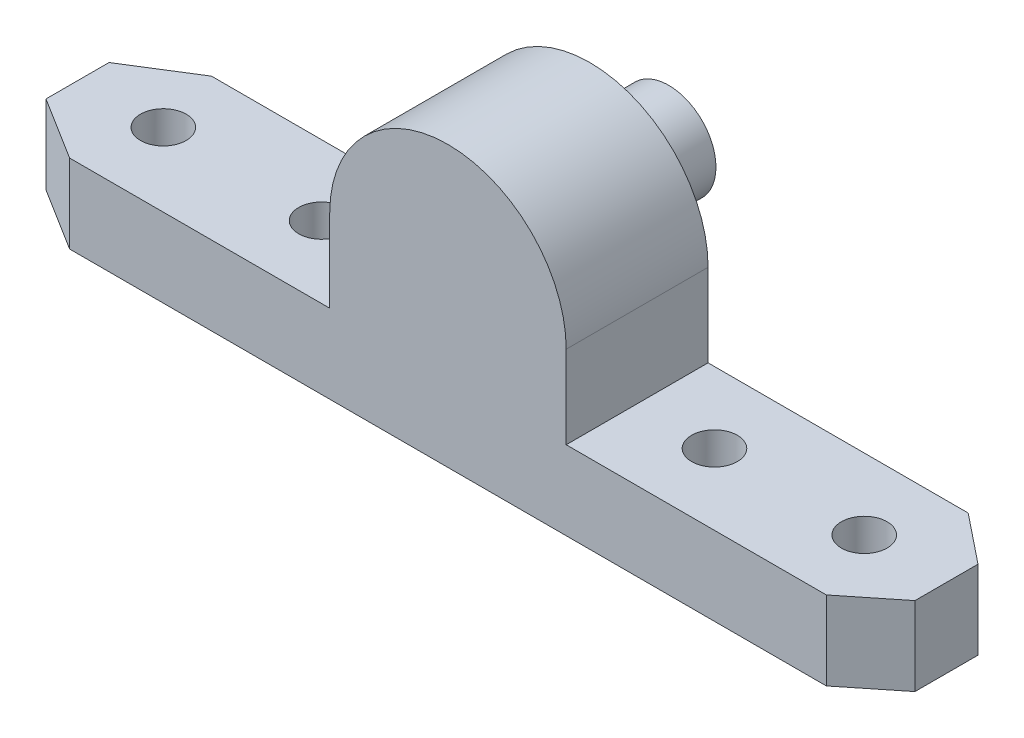
SolidWorks part; units mm, degrees
ref_plane "Płaszczyzna przednia" through (0, 0, 0) normal (0, 0, 1) x (1, 0, 0)
ref_plane "Płaszczyzna górna" through (0, 0, 0) normal (0, 1, 0) x (1, 0, 0)
ref_plane "Płaszczyzna prawa" through (0, 0, 0) normal (1, 0, 0) x (0, 0, -1)
sketch "Szkic1" plane through (0, 0, 0) normal (0, 1, 0) x (1, 0, 0)
  line L0 (24, 4.5) -> (27.1225, 2)
  line L1 (27.1225, 2) -> (27.1225, -2)
  line L2 (-24, -4.5) -> (24, -4.5)
  line L4 (-24, 4.5) -> (24, 4.5)
  line L6 (-24, -4.5) -> (24, 4.5) construction
  line L7 (-24, 4.5) -> (24, -4.5) construction
  line L8 (27.1225, -2) -> (24, -4.5)
  line L9 (-24, 4.5) -> (-28, 2)
  line L10 (-28, 2) -> (-28, -2)
  line L11 (-28, -2) -> (-24, -4.5)
  point P1 (0, 0)
  dimension "D3" = 4
  dimension "D1" = 48
  dimension "D2" = 9
  dimension "D4" = 4
  dimension "D5" = 4
  dimension "D6" = 4
  dimension "D7" = 4
  dimension "D8" = 4
extrude "Dodanie-wyciągnięcie1" add sketch "Szkic1" along normal blind 5
sketch "Szkic2" plane through (0, 0, 4.5) normal (0, 0, 1) x (1, 0, 0)
  line L0 (-24, 5) -> (24, 5) construction
  line L1 (-7.5, 5) -> (7.5, 5)
  line L2 (-7.5, 5) -> (-7.5, 10.25)
  line L4 (7.5, 10.25) -> (7.5, 5)
  arc A0 (-7.5, 10.25) -> (7.5, 10.25) centre (0, 10.25) cw
  point P7 (0, 5)
  dimension "D3" = 7.5
  dimension "D1" = 15
  dimension "D2" = 5.25
extrude "Dodanie-wyciągnięcie2" add sketch "Szkic2" against normal blind 9
sketch "Szkic3" plane through (0, 0, 4.5) normal (0, 0, 1) x (1, 0, 0)
  line L0 (0, 0) -> (0, 11) construction
  line L1 (-24, 0) -> (24, 0) construction
  circle A0 centre (0, 11) radius 3
  dimension "D2" = 6
  dimension "D1" = 11
sketch "Szkic4" plane through (0, 5, 0) normal (0, 1, 0) x (1, 0, 0)
  line L0 (27.1225, 0) -> (7.5, 0) construction
  line L1 (27.1225, -2) -> (27.1225, 2) construction
  line L2 (7.5, 4.5) -> (7.5, -4.5) construction
  line L3 (7.5, 0) -> (17.3112, 0) construction
  line L4 (17.3112, 0) -> (12.4056, 0) construction
  line L5 (12.4056, 0) -> (21.9056, 0) construction
  line L6 (-27.7881, 0.2121) -> (-7.5, 0) construction
  line L7 (-7.5, 4.5) -> (-7.5, -4.5) construction
  line L8 (-7.5, 0) -> (-17.644, 0.1061) construction
  line L9 (-17.644, 0.1061) -> (-12.572, 0.053) construction
  line L10 (-27.7881, 0.2121) -> (-17.644, 0.1061) construction
  line L11 (-17.644, 0.1061) -> (-22.716, 0.1591) construction
  circle A0 centre (12.4056, 0) radius 1.45
  circle A1 centre (21.9056, 0) radius 1.45
  circle A2 centre (-12.572, 0.053) radius 1.45
  circle A3 centre (-22.716, 0.1591) radius 1.45
  dimension "D1" = 2.9
  dimension "D3" = 2.9
  dimension "D4" = 2.9
  dimension "D5" = 2.9
  dimension "D2" = 9.5
extrude "Wytnij-wyciągnięcie1" cut sketch "Szkic4" against normal blind 6
extrude "Dodanie-wyciągnięcie3" add sketch "Szkic3" against normal blind 14
